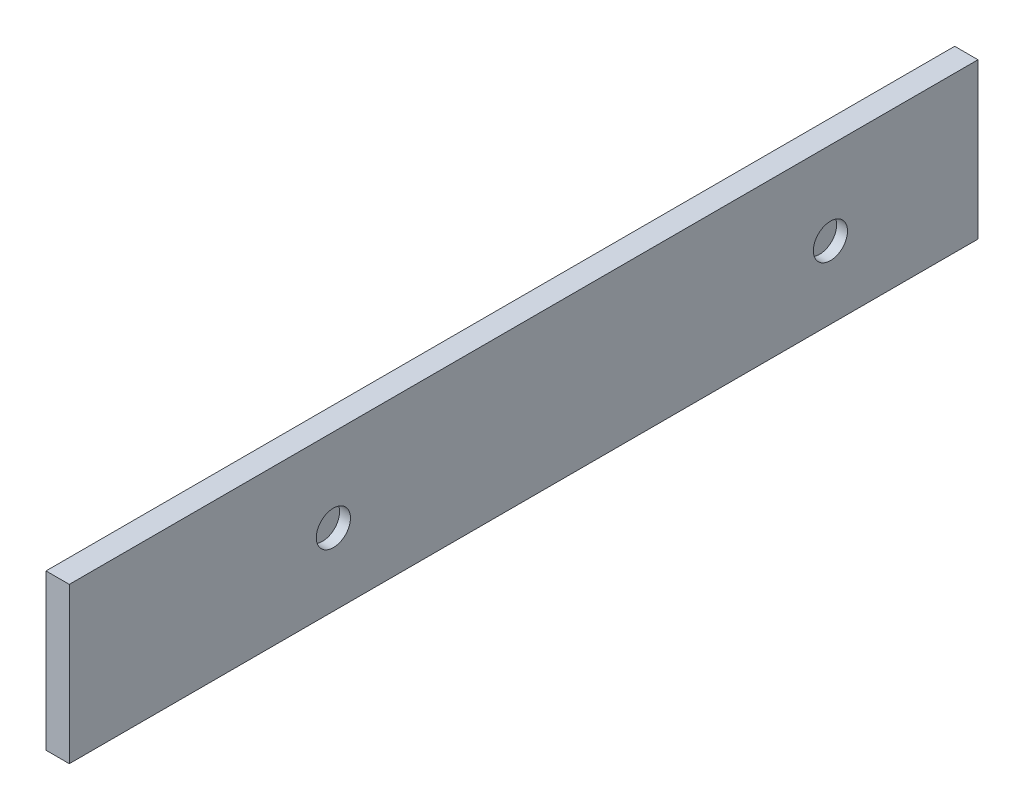
SolidWorks part; units mm, degrees
ref_plane "Alzado" through (0, 0, 0) normal (0, 0, 1) x (1, 0, 0)
ref_plane "Planta" through (0, 0, 0) normal (0, 1, 0) x (1, 0, 0)
ref_plane "Vista lateral" through (0, 0, 0) normal (1, 0, 0) x (0, 0, -1)
sketch "Croquis1" plane through (0, 0, 0) normal (1, 0, 0) x (0, 0, -1)
  line L0 (330, 100) -> (330, 0) construction
  line L1 (0, 0) -> (585, 0)
  line L2 (0, 0) -> (0, 100)
  line L3 (0, 100) -> (585, 100)
  line L4 (585, 0) -> (585, 100)
  dimension "D1" = 330
  dimension "D2" = 100
  dimension "D3" = 255
extrude "Saliente-Extruir1" add sketch "Croquis1" along normal blind 15
sketch "Croquis2" plane through (15, 0, 0) normal (1, 0, 0) x (0, 0, -1)
  line L0 (0, 0) -> (585, 0) construction
  line L1 (0, 100) -> (0, 0) construction
  line L5 (330, 100) -> (330, 0) construction
  circle A0 centre (170, 46.5) radius 11
  circle A1 centre (490, 46.5) radius 11
  dimension "D1" = 22
  dimension "D2" = 46.5
  dimension "D3" = 160
  dimension "D4" = 160
  dimension "D5" = 330
extrude "Cortar-Extruir1" cut sketch "Croquis2" against normal blind 7
